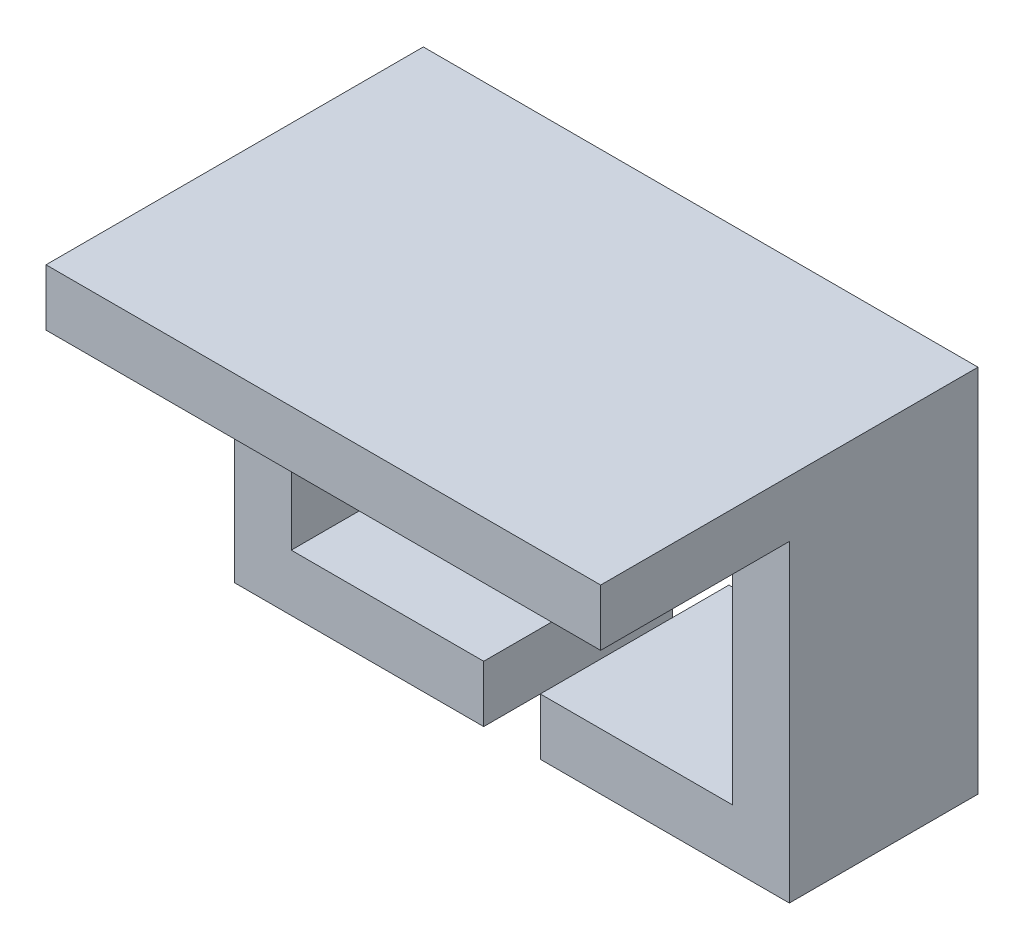
SolidWorks part; units mm, degrees
ref_plane "Спереди" through (0, 0, 0) normal (0, 0, 1) x (1, 0, 0)
ref_plane "Сверху" through (0, 0, 0) normal (0, 1, 0) x (1, 0, 0)
ref_plane "Справа" through (0, 0, 0) normal (1, 0, 0) x (0, 0, -1)
sketch "Эскиз1" plane through (0, 0, 0) normal (0, 0, 1) x (1, 0, 0)
  line L0 (-7.35, 4.9) -> (-7.35, -4.9)
  line L1 (-5.85, 3.4) -> (5.85, 3.4)
  line L2 (-5.85, 3.4) -> (-5.85, -3.4)
  line L3 (-5.85, -3.4) -> (-0.75, -3.4)
  line L4 (5.85, 3.4) -> (5.85, -3.4)
  line L5 (-5.85, 3.4) -> (5.85, -3.4) construction
  line L6 (-5.85, -3.4) -> (5.85, 3.4) construction
  line L7 (-7.35, -4.9) -> (-0.75, -4.9)
  line L8 (7.35, 4.9) -> (7.35, -4.9)
  line L9 (-7.35, 4.9) -> (7.35, 4.9)
  line L10 (-0.75, -3.4) -> (-0.75, -4.9)
  line L11 (0.75, -3.4) -> (0.75, -4.9)
  line L12 (0.75, -3.4) -> (5.85, -3.4)
  line L13 (0.75, -4.9) -> (7.35, -4.9)
  line L14 (-5.85, -3.4) -> (5.85, -3.4) construction
  line L16 (-7.35, -4.9) -> (7.35, -4.9) construction
  point P0 (0, 0)
  dimension "D1" = 11.7
  dimension "D2" = 6.8
  dimension "D4" = 1.5
  dimension "D5" = 5.1
  dimension "D3" = 1.5
extrude "Рамка по периметру" add sketch "Эскиз1" along normal blind 5
sketch "Эскиз2" plane through (0, 0, 5) normal (0, 0, 1) x (1, 0, 0)
  line L0 (7.35, -4.9) -> (7.35, 4.9) construction
  line L1 (-7.35, 4.9) -> (7.35, 4.9)
  line L2 (-7.35, 4.9) -> (-7.35, 3.4)
  line L3 (-7.35, 3.4) -> (7.35, 3.4)
  line L4 (7.35, 4.9) -> (7.35, 3.4)
  line L5 (5.85, 3.4) -> (-5.85, 3.4) construction
extrude "Выступ для крепления скотча" add sketch "Эскиз2" along normal blind 5 contours L2 L1 L4 L3
